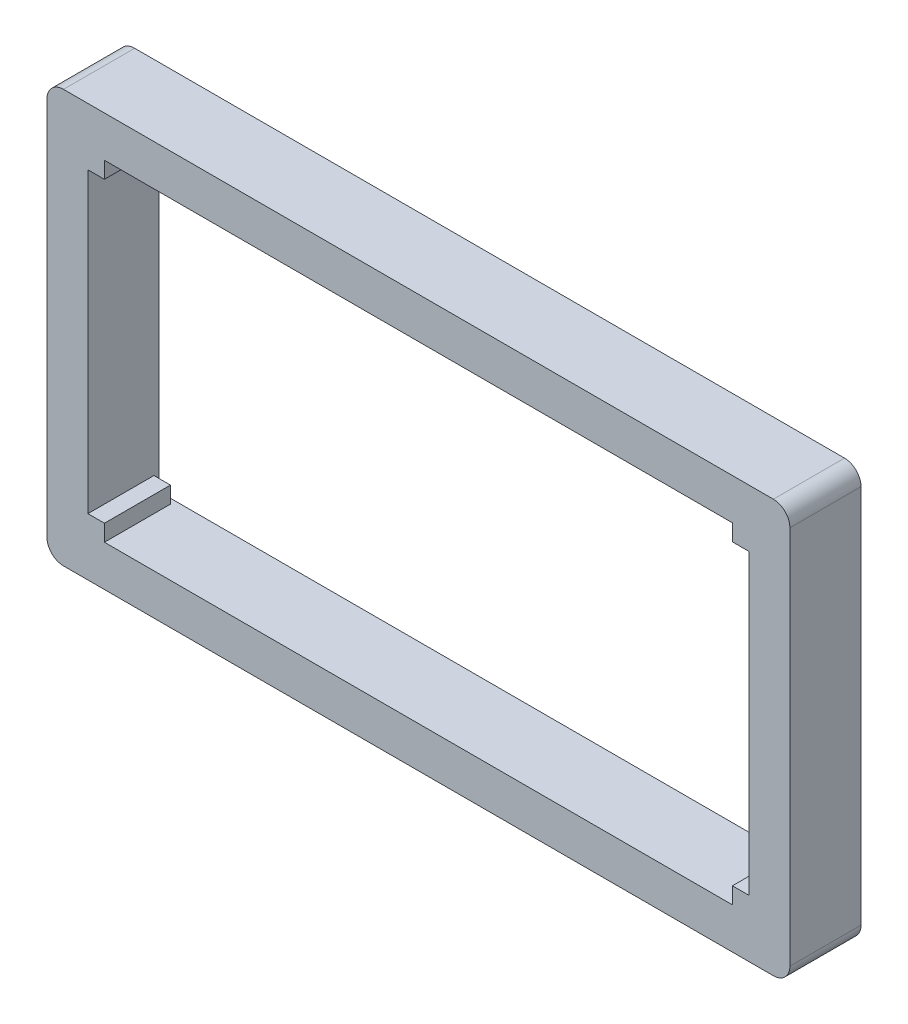
SolidWorks part; units mm, degrees
ref_plane "Front Plane" through (0, 0, 0) normal (0, 0, 1) x (1, 0, 0)
ref_plane "Top Plane" through (0, 0, 0) normal (0, 1, 0) x (1, 0, 0)
ref_plane "Right Plane" through (0, 0, 0) normal (1, 0, 0) x (0, 0, -1)
sketch "Sketch1" plane through (0, 0, 0) normal (0, 0, 1) x (1, 0, 0)
  line L1 (0, 0) -> (200.2, 0)
  line L2 (0, 0) -> (0, 100.2)
  line L3 (0, 100.2) -> (200.2, 100.2)
  line L4 (200.2, 0) -> (200.2, 100.2)
  line L5 (-12.4, 112.6) -> (212.6, 112.6)
  line L6 (-12.4, 112.6) -> (-12.4, -12.4)
  line L7 (-12.4, -12.4) -> (212.6, -12.4)
  line L8 (212.6, 112.6) -> (212.6, -12.4)
  point P9 (100.1, 100.2)
  point P10 (100.1, 112.6)
  point P11 (0, 50.1)
  point P12 (-12.4, 50.1)
  dimension "D1" = 200.2
  dimension "D2" = 100.2
  dimension "D3" = 225
  dimension "D4" = 125
extrude "Boss-Extrude1" add sketch "Sketch1" along normal blind 1.55
sketch "Sketch2" plane through (0, 0, 1.55) normal (0, 0, 1) x (1, 0, 0)
  line L1 (-12.4, 112.6) -> (212.6, 112.6)
  line L2 (-12.4, 112.6) -> (-12.4, -12.4)
  line L3 (-12.4, -12.4) -> (212.6, -12.4)
  line L4 (212.6, 112.6) -> (212.6, -12.4)
  line L5 (0, 100.2) -> (200.2, 100.2)
  line L6 (0, 100.2) -> (0, 0)
  line L7 (0, 0) -> (200.2, 0)
  line L8 (200.2, 100.2) -> (200.2, 0)
  line L9 (0, 100.2) -> (5, 100.2)
  line L10 (0, 100.2) -> (0, 95.2)
  line L11 (0, 95.2) -> (5, 95.2)
  line L12 (5, 100.2) -> (5, 95.2)
  line L13 (0, 0) -> (5, 0)
  line L14 (0, 0) -> (0, 5)
  line L15 (0, 5) -> (5, 5)
  line L16 (5, 0) -> (5, 5)
  line L17 (200.2, 100.2) -> (195.2, 100.2)
  line L18 (200.2, 100.2) -> (200.2, 95.2)
  line L19 (200.2, 95.2) -> (195.2, 95.2)
  line L20 (195.2, 100.2) -> (195.2, 95.2)
  line L21 (200.2, 0) -> (195.2, 0)
  line L22 (200.2, 0) -> (200.2, 5)
  line L23 (200.2, 5) -> (195.2, 5)
  line L24 (195.2, 0) -> (195.2, 5)
  line M23 (-12.4, 112.6) -> (-12.4, -12.4)
  line M24 (-12.4, -12.4) -> (212.6, -12.4)
  line M25 (212.6, -12.4) -> (212.6, 112.6)
  line M26 (212.6, 112.6) -> (-12.4, 112.6)
  line M27 (200.2, 0) -> (0, 0)
  line M28 (0, 0) -> (0, 100.2)
  line M29 (0, 100.2) -> (200.2, 100.2)
  line M30 (200.2, 100.2) -> (200.2, 0)
  dimension "D1" = 5
extrude "Boss-Extrude2" add sketch "Sketch2" along normal blind 20 contours L8 L7 L6 L5 M26 M23 M24 M25 M30 M27 M28 M29 | L20 L19 M29 M30 | L24 L23 M27 M30 | L13 L16 L15 L14 | L9 L12 L11 L10
fillet "Fillet1" radius 5 4 edges at (-12.4, -12.4, 10.775) (212.6, -12.4, 10.775) (-12.4, 112.6, 10.775) (212.6, 112.6, 10.775)
